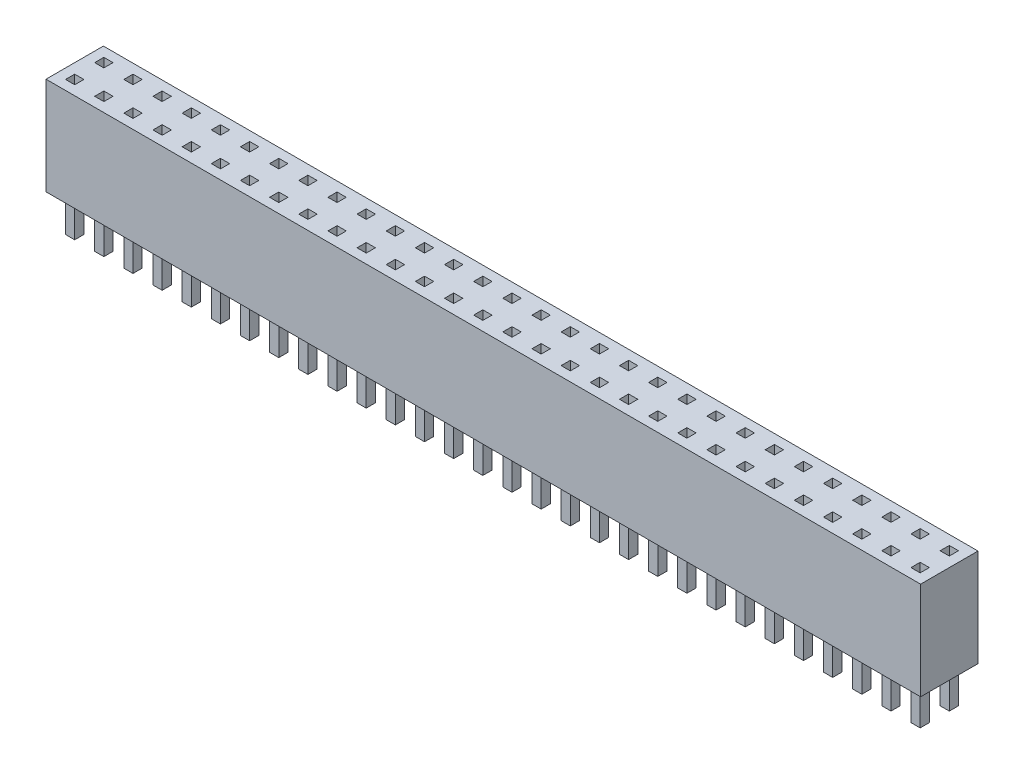
SolidWorks part; units mm, degrees
ref_plane "前视基准面" through (0, 0, 0) normal (0, 0, 1) x (1, 0, 0)
ref_plane "上视基准面" through (0, 0, 0) normal (0, 1, 0) x (1, 0, 0)
ref_plane "右视基准面" through (0, 0, 0) normal (1, 0, 0) x (0, 0, -1)
sketch "草图1" plane through (0, 0, 0) normal (0, 1, 0) x (1, 0, 0)
  line L1 (0, 0) -> (76.2, 0)
  line L2 (0, 0) -> (0, 5)
  line L3 (0, 5) -> (76.2, 5)
  line L4 (76.2, 0) -> (76.2, 5)
  dimension "D1" = 76.2
  dimension "D2" = 5
extrude "凸台-拉伸1" add sketch "草图1" along normal blind 8.5
sketch "草图3" plane through (0, 8.5, 0) normal (0, 1, 0) x (1, 0, 0)
  line L0 (0, 2.5) -> (79.2407, 2.5) construction
  line L1 (0, 5) -> (0, 0) construction
  line L2 (38.1, 5) -> (38.1, -3.0682) construction
  line L3 (76.2, 5) -> (0, 5) construction
  line L4 (3.41, 4.17) -> (4.21, 4.17)
  line L5 (0.87, 4.17) -> (1.67, 4.17)
  line L6 (0.87, 4.17) -> (0.87, 3.37)
  line L7 (0.87, 3.37) -> (1.67, 3.37)
  line L8 (1.67, 4.17) -> (1.67, 3.37)
  line L9 (3.41, 3.37) -> (4.21, 3.37)
  line L10 (4.21, 4.17) -> (4.21, 3.37)
  line L11 (3.41, 4.17) -> (3.41, 3.37)
  line L12 (5.95, 4.17) -> (6.75, 4.17)
  line L13 (5.95, 3.37) -> (6.75, 3.37)
  line L14 (6.75, 4.17) -> (6.75, 3.37)
  line L15 (5.95, 4.17) -> (5.95, 3.37)
  line L16 (8.49, 4.17) -> (9.29, 4.17)
  line L17 (8.49, 3.37) -> (9.29, 3.37)
  line L18 (9.29, 4.17) -> (9.29, 3.37)
  line L19 (8.49, 4.17) -> (8.49, 3.37)
  line L20 (11.03, 4.17) -> (11.83, 4.17)
  line L21 (11.03, 3.37) -> (11.83, 3.37)
  line L22 (11.83, 4.17) -> (11.83, 3.37)
  line L23 (11.03, 4.17) -> (11.03, 3.37)
  line L24 (13.57, 4.17) -> (14.37, 4.17)
  line L25 (13.57, 3.37) -> (14.37, 3.37)
  line L26 (14.37, 4.17) -> (14.37, 3.37)
  line L27 (13.57, 4.17) -> (13.57, 3.37)
  line L28 (16.11, 4.17) -> (16.91, 4.17)
  line L29 (16.11, 3.37) -> (16.91, 3.37)
  line L30 (16.91, 4.17) -> (16.91, 3.37)
  line L31 (16.11, 4.17) -> (16.11, 3.37)
  line L32 (18.65, 4.17) -> (19.45, 4.17)
  line L33 (18.65, 3.37) -> (19.45, 3.37)
  line L34 (19.45, 4.17) -> (19.45, 3.37)
  line L35 (18.65, 4.17) -> (18.65, 3.37)
  line L36 (21.19, 4.17) -> (21.99, 4.17)
  line L37 (21.19, 3.37) -> (21.99, 3.37)
  line L38 (21.99, 4.17) -> (21.99, 3.37)
  line L39 (21.19, 4.17) -> (21.19, 3.37)
  line L40 (23.73, 4.17) -> (24.53, 4.17)
  line L41 (23.73, 3.37) -> (24.53, 3.37)
  line L42 (24.53, 4.17) -> (24.53, 3.37)
  line L43 (23.73, 4.17) -> (23.73, 3.37)
  line L44 (26.27, 4.17) -> (27.07, 4.17)
  line L45 (26.27, 3.37) -> (27.07, 3.37)
  line L46 (27.07, 4.17) -> (27.07, 3.37)
  line L47 (26.27, 4.17) -> (26.27, 3.37)
  line L48 (28.81, 4.17) -> (29.61, 4.17)
  line L49 (28.81, 3.37) -> (29.61, 3.37)
  line L50 (29.61, 4.17) -> (29.61, 3.37)
  line L51 (28.81, 4.17) -> (28.81, 3.37)
  line L52 (31.35, 4.17) -> (32.15, 4.17)
  line L53 (31.35, 3.37) -> (32.15, 3.37)
  line L54 (32.15, 4.17) -> (32.15, 3.37)
  line L55 (31.35, 4.17) -> (31.35, 3.37)
  line L56 (33.89, 4.17) -> (34.69, 4.17)
  line L57 (33.89, 3.37) -> (34.69, 3.37)
  line L58 (34.69, 4.17) -> (34.69, 3.37)
  line L59 (33.89, 4.17) -> (33.89, 3.37)
  line L60 (36.43, 4.17) -> (37.23, 4.17)
  line L61 (36.43, 3.37) -> (37.23, 3.37)
  line L62 (37.23, 4.17) -> (37.23, 3.37)
  line L63 (36.43, 4.17) -> (36.43, 3.37)
  line L64 (38.97, 4.17) -> (39.77, 4.17)
  line L65 (38.97, 3.37) -> (39.77, 3.37)
  line L66 (39.77, 4.17) -> (39.77, 3.37)
  line L67 (38.97, 4.17) -> (38.97, 3.37)
  line L68 (41.51, 4.17) -> (42.31, 4.17)
  line L69 (41.51, 3.37) -> (42.31, 3.37)
  line L70 (42.31, 4.17) -> (42.31, 3.37)
  line L71 (41.51, 4.17) -> (41.51, 3.37)
  line L72 (44.05, 4.17) -> (44.85, 4.17)
  line L73 (44.05, 3.37) -> (44.85, 3.37)
  line L74 (44.85, 4.17) -> (44.85, 3.37)
  line L75 (44.05, 4.17) -> (44.05, 3.37)
  line L76 (46.59, 4.17) -> (47.39, 4.17)
  line L77 (46.59, 3.37) -> (47.39, 3.37)
  line L78 (47.39, 4.17) -> (47.39, 3.37)
  line L79 (46.59, 4.17) -> (46.59, 3.37)
  line L80 (49.13, 4.17) -> (49.93, 4.17)
  line L81 (49.13, 3.37) -> (49.93, 3.37)
  line L82 (49.93, 4.17) -> (49.93, 3.37)
  line L83 (49.13, 4.17) -> (49.13, 3.37)
  line L84 (51.67, 4.17) -> (52.47, 4.17)
  line L85 (51.67, 3.37) -> (52.47, 3.37)
  line L86 (52.47, 4.17) -> (52.47, 3.37)
  line L87 (51.67, 4.17) -> (51.67, 3.37)
  line L88 (54.21, 4.17) -> (55.01, 4.17)
  line L89 (54.21, 3.37) -> (55.01, 3.37)
  line L90 (55.01, 4.17) -> (55.01, 3.37)
  line L91 (54.21, 4.17) -> (54.21, 3.37)
  line L92 (56.75, 4.17) -> (57.55, 4.17)
  line L93 (56.75, 3.37) -> (57.55, 3.37)
  line L94 (57.55, 4.17) -> (57.55, 3.37)
  line L95 (56.75, 4.17) -> (56.75, 3.37)
  line L96 (59.29, 4.17) -> (60.09, 4.17)
  line L97 (59.29, 3.37) -> (60.09, 3.37)
  line L98 (60.09, 4.17) -> (60.09, 3.37)
  line L99 (59.29, 4.17) -> (59.29, 3.37)
  line L100 (61.83, 4.17) -> (62.63, 4.17)
  line L101 (61.83, 3.37) -> (62.63, 3.37)
  line L102 (62.63, 4.17) -> (62.63, 3.37)
  line L103 (61.83, 4.17) -> (61.83, 3.37)
  line L104 (64.37, 4.17) -> (65.17, 4.17)
  line L105 (64.37, 3.37) -> (65.17, 3.37)
  line L106 (65.17, 4.17) -> (65.17, 3.37)
  line L107 (64.37, 4.17) -> (64.37, 3.37)
  line L108 (66.91, 4.17) -> (67.71, 4.17)
  line L109 (66.91, 3.37) -> (67.71, 3.37)
  line L110 (67.71, 4.17) -> (67.71, 3.37)
  line L111 (66.91, 4.17) -> (66.91, 3.37)
  line L112 (69.45, 4.17) -> (70.25, 4.17)
  line L113 (69.45, 3.37) -> (70.25, 3.37)
  line L114 (70.25, 4.17) -> (70.25, 3.37)
  line L115 (69.45, 4.17) -> (69.45, 3.37)
  line L116 (71.99, 4.17) -> (72.79, 4.17)
  line L117 (71.99, 3.37) -> (72.79, 3.37)
  line L118 (72.79, 4.17) -> (72.79, 3.37)
  line L119 (71.99, 4.17) -> (71.99, 3.37)
  line L120 (74.53, 4.17) -> (75.33, 4.17)
  line L121 (74.53, 3.37) -> (75.33, 3.37)
  line L122 (75.33, 4.17) -> (75.33, 3.37)
  line L123 (74.53, 4.17) -> (74.53, 3.37)
  line L124 (3.41, 1.63) -> (4.21, 1.63)
  line L125 (3.41, 0.83) -> (4.21, 0.83)
  line L126 (4.21, 1.63) -> (4.21, 0.83)
  line L127 (3.41, 1.63) -> (3.41, 0.83)
  line L128 (5.95, 1.63) -> (6.75, 1.63)
  line L129 (5.95, 0.83) -> (6.75, 0.83)
  line L130 (6.75, 1.63) -> (6.75, 0.83)
  line L131 (5.95, 1.63) -> (5.95, 0.83)
  line L132 (8.49, 1.63) -> (9.29, 1.63)
  line L133 (8.49, 0.83) -> (9.29, 0.83)
  line L134 (9.29, 1.63) -> (9.29, 0.83)
  line L135 (8.49, 1.63) -> (8.49, 0.83)
  line L136 (11.03, 1.63) -> (11.83, 1.63)
  line L137 (11.03, 0.83) -> (11.83, 0.83)
  line L138 (11.83, 1.63) -> (11.83, 0.83)
  line L139 (11.03, 1.63) -> (11.03, 0.83)
  line L140 (13.57, 1.63) -> (14.37, 1.63)
  line L141 (13.57, 0.83) -> (14.37, 0.83)
  line L142 (14.37, 1.63) -> (14.37, 0.83)
  line L143 (13.57, 1.63) -> (13.57, 0.83)
  line L144 (16.11, 1.63) -> (16.91, 1.63)
  line L145 (16.11, 0.83) -> (16.91, 0.83)
  line L146 (16.91, 1.63) -> (16.91, 0.83)
  line L147 (16.11, 1.63) -> (16.11, 0.83)
  line L148 (18.65, 1.63) -> (19.45, 1.63)
  line L149 (18.65, 0.83) -> (19.45, 0.83)
  line L150 (19.45, 1.63) -> (19.45, 0.83)
  line L151 (18.65, 1.63) -> (18.65, 0.83)
  line L152 (21.19, 1.63) -> (21.99, 1.63)
  line L153 (21.19, 0.83) -> (21.99, 0.83)
  line L154 (21.99, 1.63) -> (21.99, 0.83)
  line L155 (21.19, 1.63) -> (21.19, 0.83)
  line L156 (23.73, 1.63) -> (24.53, 1.63)
  line L157 (23.73, 0.83) -> (24.53, 0.83)
  line L158 (24.53, 1.63) -> (24.53, 0.83)
  line L159 (23.73, 1.63) -> (23.73, 0.83)
  line L160 (26.27, 1.63) -> (27.07, 1.63)
  line L161 (26.27, 0.83) -> (27.07, 0.83)
  line L162 (27.07, 1.63) -> (27.07, 0.83)
  line L163 (26.27, 1.63) -> (26.27, 0.83)
  line L164 (28.81, 1.63) -> (29.61, 1.63)
  line L165 (28.81, 0.83) -> (29.61, 0.83)
  line L166 (29.61, 1.63) -> (29.61, 0.83)
  line L167 (28.81, 1.63) -> (28.81, 0.83)
  line L168 (31.35, 1.63) -> (32.15, 1.63)
  line L169 (31.35, 0.83) -> (32.15, 0.83)
  line L170 (32.15, 1.63) -> (32.15, 0.83)
  line L171 (31.35, 1.63) -> (31.35, 0.83)
  line L172 (33.89, 1.63) -> (34.69, 1.63)
  line L173 (33.89, 0.83) -> (34.69, 0.83)
  line L174 (34.69, 1.63) -> (34.69, 0.83)
  line L175 (33.89, 1.63) -> (33.89, 0.83)
  line L176 (36.43, 1.63) -> (37.23, 1.63)
  line L177 (36.43, 0.83) -> (37.23, 0.83)
  line L178 (37.23, 1.63) -> (37.23, 0.83)
  line L179 (36.43, 1.63) -> (36.43, 0.83)
  line L180 (38.97, 1.63) -> (39.77, 1.63)
  line L181 (38.97, 0.83) -> (39.77, 0.83)
  line L182 (39.77, 1.63) -> (39.77, 0.83)
  line L183 (38.97, 1.63) -> (38.97, 0.83)
  line L184 (41.51, 1.63) -> (42.31, 1.63)
  line L185 (41.51, 0.83) -> (42.31, 0.83)
  line L186 (42.31, 1.63) -> (42.31, 0.83)
  line L187 (41.51, 1.63) -> (41.51, 0.83)
  line L188 (44.05, 1.63) -> (44.85, 1.63)
  line L189 (44.05, 0.83) -> (44.85, 0.83)
  line L190 (44.85, 1.63) -> (44.85, 0.83)
  line L191 (44.05, 1.63) -> (44.05, 0.83)
  line L192 (46.59, 1.63) -> (47.39, 1.63)
  line L193 (46.59, 0.83) -> (47.39, 0.83)
  line L194 (47.39, 1.63) -> (47.39, 0.83)
  line L195 (46.59, 1.63) -> (46.59, 0.83)
  line L196 (49.13, 1.63) -> (49.93, 1.63)
  line L197 (49.13, 0.83) -> (49.93, 0.83)
  line L198 (49.93, 1.63) -> (49.93, 0.83)
  line L199 (49.13, 1.63) -> (49.13, 0.83)
  line L200 (51.67, 1.63) -> (52.47, 1.63)
  line L201 (51.67, 0.83) -> (52.47, 0.83)
  line L202 (52.47, 1.63) -> (52.47, 0.83)
  line L203 (51.67, 1.63) -> (51.67, 0.83)
  line L204 (54.21, 1.63) -> (55.01, 1.63)
  line L205 (54.21, 0.83) -> (55.01, 0.83)
  line L206 (55.01, 1.63) -> (55.01, 0.83)
  line L207 (54.21, 1.63) -> (54.21, 0.83)
  line L208 (56.75, 1.63) -> (57.55, 1.63)
  line L209 (56.75, 0.83) -> (57.55, 0.83)
  line L210 (57.55, 1.63) -> (57.55, 0.83)
  line L211 (56.75, 1.63) -> (56.75, 0.83)
  line L212 (59.29, 1.63) -> (60.09, 1.63)
  line L213 (59.29, 0.83) -> (60.09, 0.83)
  line L214 (60.09, 1.63) -> (60.09, 0.83)
  line L215 (59.29, 1.63) -> (59.29, 0.83)
  line L216 (61.83, 1.63) -> (62.63, 1.63)
  line L217 (61.83, 0.83) -> (62.63, 0.83)
  line L218 (62.63, 1.63) -> (62.63, 0.83)
  line L219 (61.83, 1.63) -> (61.83, 0.83)
  line L220 (64.37, 1.63) -> (65.17, 1.63)
  line L221 (64.37, 0.83) -> (65.17, 0.83)
  line L222 (65.17, 1.63) -> (65.17, 0.83)
  line L223 (64.37, 1.63) -> (64.37, 0.83)
  line L224 (66.91, 1.63) -> (67.71, 1.63)
  line L225 (66.91, 0.83) -> (67.71, 0.83)
  line L226 (67.71, 1.63) -> (67.71, 0.83)
  line L227 (66.91, 1.63) -> (66.91, 0.83)
  line L228 (69.45, 1.63) -> (70.25, 1.63)
  line L229 (69.45, 0.83) -> (70.25, 0.83)
  line L230 (70.25, 1.63) -> (70.25, 0.83)
  line L231 (69.45, 1.63) -> (69.45, 0.83)
  line L232 (71.99, 1.63) -> (72.79, 1.63)
  line L233 (71.99, 0.83) -> (72.79, 0.83)
  line L234 (72.79, 1.63) -> (72.79, 0.83)
  line L235 (71.99, 1.63) -> (71.99, 0.83)
  line L236 (74.53, 1.63) -> (75.33, 1.63)
  line L237 (74.53, 0.83) -> (75.33, 0.83)
  line L238 (75.33, 1.63) -> (75.33, 0.83)
  line L239 (74.53, 1.63) -> (74.53, 0.83)
  line L240 (0.87, 1.63) -> (1.67, 1.63)
  line L241 (0.87, 0.83) -> (1.67, 0.83)
  line L242 (1.67, 1.63) -> (1.67, 0.83)
  line L243 (0.87, 1.63) -> (0.87, 0.83)
  dimension "D1" = 0.8
  dimension "D2" = 0.87
  dimension "D3" = 0.87
  dimension "D6" = 2.54
  dimension "D7" = 2.54
  dimension "D4" = 30
  dimension "D5" = 2
extrude "切除-拉伸1" cut sketch "草图3" against normal blind 8
sketch "草图4" plane through (0, 0, 0) normal (0, -1, 0) x (1, 0, 0)
  line L0 (3.41, -3.37) -> (3.41, -4.17)
  line L1 (0.87, -0.83) -> (1.67, -0.83)
  line L2 (0.87, -0.83) -> (0.87, -1.63)
  line L3 (0.87, -1.63) -> (1.67, -1.63)
  line L4 (1.67, -0.83) -> (1.67, -1.63)
  line L5 (0.87, -3.37) -> (1.67, -3.37)
  line L6 (0.87, -3.37) -> (0.87, -4.17)
  line L7 (0.87, -4.17) -> (1.67, -4.17)
  line L8 (1.67, -3.37) -> (1.67, -4.17)
  line L9 (3.41, -3.37) -> (4.21, -3.37)
  line L10 (4.21, -3.37) -> (4.21, -4.17)
  line L11 (3.41, -4.17) -> (4.21, -4.17)
  line L12 (3.41, -0.83) -> (4.21, -0.83)
  line L13 (4.21, -0.83) -> (4.21, -1.63)
  line L14 (3.41, -0.83) -> (3.41, -1.63)
  line L15 (3.41, -1.63) -> (4.21, -1.63)
  line L16 (5.95, -3.37) -> (5.95, -4.17)
  line L17 (5.95, -3.37) -> (6.75, -3.37)
  line L18 (6.75, -3.37) -> (6.75, -4.17)
  line L19 (5.95, -4.17) -> (6.75, -4.17)
  line L20 (5.95, -0.83) -> (6.75, -0.83)
  line L21 (6.75, -0.83) -> (6.75, -1.63)
  line L22 (5.95, -0.83) -> (5.95, -1.63)
  line L23 (5.95, -1.63) -> (6.75, -1.63)
  line L24 (8.49, -3.37) -> (8.49, -4.17)
  line L25 (8.49, -3.37) -> (9.29, -3.37)
  line L26 (9.29, -3.37) -> (9.29, -4.17)
  line L27 (8.49, -4.17) -> (9.29, -4.17)
  line L28 (8.49, -0.83) -> (9.29, -0.83)
  line L29 (9.29, -0.83) -> (9.29, -1.63)
  line L30 (8.49, -0.83) -> (8.49, -1.63)
  line L31 (8.49, -1.63) -> (9.29, -1.63)
  line L32 (11.03, -3.37) -> (11.03, -4.17)
  line L33 (11.03, -3.37) -> (11.83, -3.37)
  line L34 (11.83, -3.37) -> (11.83, -4.17)
  line L35 (11.03, -4.17) -> (11.83, -4.17)
  line L36 (11.03, -0.83) -> (11.83, -0.83)
  line L37 (11.83, -0.83) -> (11.83, -1.63)
  line L38 (11.03, -0.83) -> (11.03, -1.63)
  line L39 (11.03, -1.63) -> (11.83, -1.63)
  line L40 (13.57, -3.37) -> (13.57, -4.17)
  line L41 (13.57, -3.37) -> (14.37, -3.37)
  line L42 (14.37, -3.37) -> (14.37, -4.17)
  line L43 (13.57, -4.17) -> (14.37, -4.17)
  line L44 (13.57, -0.83) -> (14.37, -0.83)
  line L45 (14.37, -0.83) -> (14.37, -1.63)
  line L46 (13.57, -0.83) -> (13.57, -1.63)
  line L47 (13.57, -1.63) -> (14.37, -1.63)
  line L48 (16.11, -3.37) -> (16.11, -4.17)
  line L49 (16.11, -3.37) -> (16.91, -3.37)
  line L50 (16.91, -3.37) -> (16.91, -4.17)
  line L51 (16.11, -4.17) -> (16.91, -4.17)
  line L52 (16.11, -0.83) -> (16.91, -0.83)
  line L53 (16.91, -0.83) -> (16.91, -1.63)
  line L54 (16.11, -0.83) -> (16.11, -1.63)
  line L55 (16.11, -1.63) -> (16.91, -1.63)
  line L56 (18.65, -3.37) -> (18.65, -4.17)
  line L57 (18.65, -3.37) -> (19.45, -3.37)
  line L58 (19.45, -3.37) -> (19.45, -4.17)
  line L59 (18.65, -4.17) -> (19.45, -4.17)
  line L60 (18.65, -0.83) -> (19.45, -0.83)
  line L61 (19.45, -0.83) -> (19.45, -1.63)
  line L62 (18.65, -0.83) -> (18.65, -1.63)
  line L63 (18.65, -1.63) -> (19.45, -1.63)
  line L64 (21.19, -3.37) -> (21.19, -4.17)
  line L65 (21.19, -3.37) -> (21.99, -3.37)
  line L66 (21.99, -3.37) -> (21.99, -4.17)
  line L67 (21.19, -4.17) -> (21.99, -4.17)
  line L68 (21.19, -0.83) -> (21.99, -0.83)
  line L69 (21.99, -0.83) -> (21.99, -1.63)
  line L70 (21.19, -0.83) -> (21.19, -1.63)
  line L71 (21.19, -1.63) -> (21.99, -1.63)
  line L72 (23.73, -3.37) -> (23.73, -4.17)
  line L73 (23.73, -3.37) -> (24.53, -3.37)
  line L74 (24.53, -3.37) -> (24.53, -4.17)
  line L75 (23.73, -4.17) -> (24.53, -4.17)
  line L76 (23.73, -0.83) -> (24.53, -0.83)
  line L77 (24.53, -0.83) -> (24.53, -1.63)
  line L78 (23.73, -0.83) -> (23.73, -1.63)
  line L79 (23.73, -1.63) -> (24.53, -1.63)
  line L80 (26.27, -3.37) -> (26.27, -4.17)
  line L81 (26.27, -3.37) -> (27.07, -3.37)
  line L82 (27.07, -3.37) -> (27.07, -4.17)
  line L83 (26.27, -4.17) -> (27.07, -4.17)
  line L84 (26.27, -0.83) -> (27.07, -0.83)
  line L85 (27.07, -0.83) -> (27.07, -1.63)
  line L86 (26.27, -0.83) -> (26.27, -1.63)
  line L87 (26.27, -1.63) -> (27.07, -1.63)
  line L88 (28.81, -3.37) -> (28.81, -4.17)
  line L89 (28.81, -3.37) -> (29.61, -3.37)
  line L90 (29.61, -3.37) -> (29.61, -4.17)
  line L91 (28.81, -4.17) -> (29.61, -4.17)
  line L92 (28.81, -0.83) -> (29.61, -0.83)
  line L93 (29.61, -0.83) -> (29.61, -1.63)
  line L94 (28.81, -0.83) -> (28.81, -1.63)
  line L95 (28.81, -1.63) -> (29.61, -1.63)
  line L96 (31.35, -3.37) -> (31.35, -4.17)
  line L97 (31.35, -3.37) -> (32.15, -3.37)
  line L98 (32.15, -3.37) -> (32.15, -4.17)
  line L99 (31.35, -4.17) -> (32.15, -4.17)
  line L100 (31.35, -0.83) -> (32.15, -0.83)
  line L101 (32.15, -0.83) -> (32.15, -1.63)
  line L102 (31.35, -0.83) -> (31.35, -1.63)
  line L103 (31.35, -1.63) -> (32.15, -1.63)
  line L104 (33.89, -3.37) -> (33.89, -4.17)
  line L105 (33.89, -3.37) -> (34.69, -3.37)
  line L106 (34.69, -3.37) -> (34.69, -4.17)
  line L107 (33.89, -4.17) -> (34.69, -4.17)
  line L108 (33.89, -0.83) -> (34.69, -0.83)
  line L109 (34.69, -0.83) -> (34.69, -1.63)
  line L110 (33.89, -0.83) -> (33.89, -1.63)
  line L111 (33.89, -1.63) -> (34.69, -1.63)
  line L112 (36.43, -3.37) -> (36.43, -4.17)
  line L113 (36.43, -3.37) -> (37.23, -3.37)
  line L114 (37.23, -3.37) -> (37.23, -4.17)
  line L115 (36.43, -4.17) -> (37.23, -4.17)
  line L116 (36.43, -0.83) -> (37.23, -0.83)
  line L117 (37.23, -0.83) -> (37.23, -1.63)
  line L118 (36.43, -0.83) -> (36.43, -1.63)
  line L119 (36.43, -1.63) -> (37.23, -1.63)
  line L120 (38.97, -3.37) -> (38.97, -4.17)
  line L121 (38.97, -3.37) -> (39.77, -3.37)
  line L122 (39.77, -3.37) -> (39.77, -4.17)
  line L123 (38.97, -4.17) -> (39.77, -4.17)
  line L124 (38.97, -0.83) -> (39.77, -0.83)
  line L125 (39.77, -0.83) -> (39.77, -1.63)
  line L126 (38.97, -0.83) -> (38.97, -1.63)
  line L127 (38.97, -1.63) -> (39.77, -1.63)
  line L128 (41.51, -3.37) -> (41.51, -4.17)
  line L129 (41.51, -3.37) -> (42.31, -3.37)
  line L130 (42.31, -3.37) -> (42.31, -4.17)
  line L131 (41.51, -4.17) -> (42.31, -4.17)
  line L132 (41.51, -0.83) -> (42.31, -0.83)
  line L133 (42.31, -0.83) -> (42.31, -1.63)
  line L134 (41.51, -0.83) -> (41.51, -1.63)
  line L135 (41.51, -1.63) -> (42.31, -1.63)
  line L136 (44.05, -3.37) -> (44.05, -4.17)
  line L137 (44.05, -3.37) -> (44.85, -3.37)
  line L138 (44.85, -3.37) -> (44.85, -4.17)
  line L139 (44.05, -4.17) -> (44.85, -4.17)
  line L140 (44.05, -0.83) -> (44.85, -0.83)
  line L141 (44.85, -0.83) -> (44.85, -1.63)
  line L142 (44.05, -0.83) -> (44.05, -1.63)
  line L143 (44.05, -1.63) -> (44.85, -1.63)
  line L144 (46.59, -3.37) -> (46.59, -4.17)
  line L145 (46.59, -3.37) -> (47.39, -3.37)
  line L146 (47.39, -3.37) -> (47.39, -4.17)
  line L147 (46.59, -4.17) -> (47.39, -4.17)
  line L148 (46.59, -0.83) -> (47.39, -0.83)
  line L149 (47.39, -0.83) -> (47.39, -1.63)
  line L150 (46.59, -0.83) -> (46.59, -1.63)
  line L151 (46.59, -1.63) -> (47.39, -1.63)
  line L152 (49.13, -3.37) -> (49.13, -4.17)
  line L153 (49.13, -3.37) -> (49.93, -3.37)
  line L154 (49.93, -3.37) -> (49.93, -4.17)
  line L155 (49.13, -4.17) -> (49.93, -4.17)
  line L156 (49.13, -0.83) -> (49.93, -0.83)
  line L157 (49.93, -0.83) -> (49.93, -1.63)
  line L158 (49.13, -0.83) -> (49.13, -1.63)
  line L159 (49.13, -1.63) -> (49.93, -1.63)
  line L160 (51.67, -3.37) -> (51.67, -4.17)
  line L161 (51.67, -3.37) -> (52.47, -3.37)
  line L162 (52.47, -3.37) -> (52.47, -4.17)
  line L163 (51.67, -4.17) -> (52.47, -4.17)
  line L164 (51.67, -0.83) -> (52.47, -0.83)
  line L165 (52.47, -0.83) -> (52.47, -1.63)
  line L166 (51.67, -0.83) -> (51.67, -1.63)
  line L167 (51.67, -1.63) -> (52.47, -1.63)
  line L168 (54.21, -3.37) -> (54.21, -4.17)
  line L169 (54.21, -3.37) -> (55.01, -3.37)
  line L170 (55.01, -3.37) -> (55.01, -4.17)
  line L171 (54.21, -4.17) -> (55.01, -4.17)
  line L172 (54.21, -0.83) -> (55.01, -0.83)
  line L173 (55.01, -0.83) -> (55.01, -1.63)
  line L174 (54.21, -0.83) -> (54.21, -1.63)
  line L175 (54.21, -1.63) -> (55.01, -1.63)
  line L176 (56.75, -3.37) -> (56.75, -4.17)
  line L177 (56.75, -3.37) -> (57.55, -3.37)
  line L178 (57.55, -3.37) -> (57.55, -4.17)
  line L179 (56.75, -4.17) -> (57.55, -4.17)
  line L180 (56.75, -0.83) -> (57.55, -0.83)
  line L181 (57.55, -0.83) -> (57.55, -1.63)
  line L182 (56.75, -0.83) -> (56.75, -1.63)
  line L183 (56.75, -1.63) -> (57.55, -1.63)
  line L184 (59.29, -3.37) -> (59.29, -4.17)
  line L185 (59.29, -3.37) -> (60.09, -3.37)
  line L186 (60.09, -3.37) -> (60.09, -4.17)
  line L187 (59.29, -4.17) -> (60.09, -4.17)
  line L188 (59.29, -0.83) -> (60.09, -0.83)
  line L189 (60.09, -0.83) -> (60.09, -1.63)
  line L190 (59.29, -0.83) -> (59.29, -1.63)
  line L191 (59.29, -1.63) -> (60.09, -1.63)
  line L192 (61.83, -3.37) -> (61.83, -4.17)
  line L193 (61.83, -3.37) -> (62.63, -3.37)
  line L194 (62.63, -3.37) -> (62.63, -4.17)
  line L195 (61.83, -4.17) -> (62.63, -4.17)
  line L196 (61.83, -0.83) -> (62.63, -0.83)
  line L197 (62.63, -0.83) -> (62.63, -1.63)
  line L198 (61.83, -0.83) -> (61.83, -1.63)
  line L199 (61.83, -1.63) -> (62.63, -1.63)
  line L200 (64.37, -3.37) -> (64.37, -4.17)
  line L201 (64.37, -3.37) -> (65.17, -3.37)
  line L202 (65.17, -3.37) -> (65.17, -4.17)
  line L203 (64.37, -4.17) -> (65.17, -4.17)
  line L204 (64.37, -0.83) -> (65.17, -0.83)
  line L205 (65.17, -0.83) -> (65.17, -1.63)
  line L206 (64.37, -0.83) -> (64.37, -1.63)
  line L207 (64.37, -1.63) -> (65.17, -1.63)
  line L208 (66.91, -3.37) -> (66.91, -4.17)
  line L209 (66.91, -3.37) -> (67.71, -3.37)
  line L210 (67.71, -3.37) -> (67.71, -4.17)
  line L211 (66.91, -4.17) -> (67.71, -4.17)
  line L212 (66.91, -0.83) -> (67.71, -0.83)
  line L213 (67.71, -0.83) -> (67.71, -1.63)
  line L214 (66.91, -0.83) -> (66.91, -1.63)
  line L215 (66.91, -1.63) -> (67.71, -1.63)
  line L216 (69.45, -3.37) -> (69.45, -4.17)
  line L217 (69.45, -3.37) -> (70.25, -3.37)
  line L218 (70.25, -3.37) -> (70.25, -4.17)
  line L219 (69.45, -4.17) -> (70.25, -4.17)
  line L220 (69.45, -0.83) -> (70.25, -0.83)
  line L221 (70.25, -0.83) -> (70.25, -1.63)
  line L222 (69.45, -0.83) -> (69.45, -1.63)
  line L223 (69.45, -1.63) -> (70.25, -1.63)
  line L224 (71.99, -3.37) -> (71.99, -4.17)
  line L225 (71.99, -3.37) -> (72.79, -3.37)
  line L226 (72.79, -3.37) -> (72.79, -4.17)
  line L227 (71.99, -4.17) -> (72.79, -4.17)
  line L228 (71.99, -0.83) -> (72.79, -0.83)
  line L229 (72.79, -0.83) -> (72.79, -1.63)
  line L230 (71.99, -0.83) -> (71.99, -1.63)
  line L231 (71.99, -1.63) -> (72.79, -1.63)
  line L232 (74.53, -3.37) -> (74.53, -4.17)
  line L233 (74.53, -3.37) -> (75.33, -3.37)
  line L234 (75.33, -3.37) -> (75.33, -4.17)
  line L235 (74.53, -4.17) -> (75.33, -4.17)
  line L236 (74.53, -0.83) -> (75.33, -0.83)
  line L237 (75.33, -0.83) -> (75.33, -1.63)
  line L238 (74.53, -0.83) -> (74.53, -1.63)
  line L239 (74.53, -1.63) -> (75.33, -1.63)
  point P12 (4.21, -1.23)
  dimension "D2" = 2.54
  dimension "D1" = 30
extrude "凸台-拉伸2" add sketch "草图4" along normal blind 3.2
